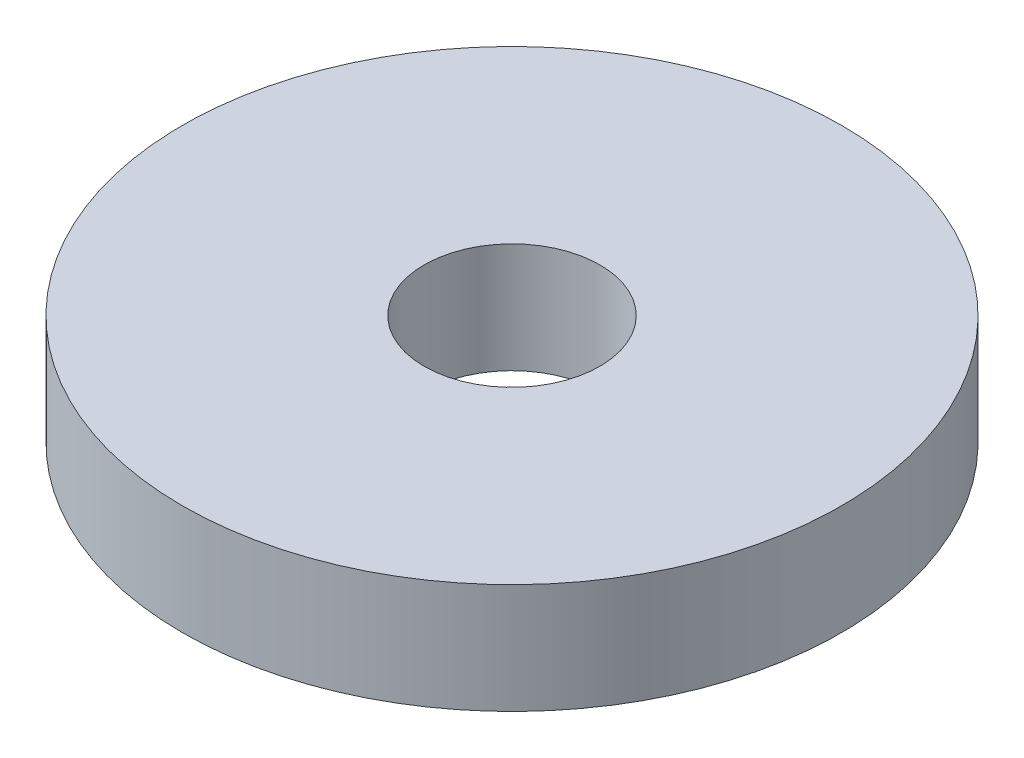
SolidWorks part; units mm, degrees
ref_plane "Front Plane" through (0, 0, 0) normal (0, 0, 1) x (1, 0, 0)
ref_plane "Top Plane" through (0, 0, 0) normal (0, 1, 0) x (1, 0, 0)
ref_plane "Right Plane" through (0, 0, 0) normal (1, 0, 0) x (0, 0, -1)
sketch "Sketch1" plane through (0, 0, 0) normal (0, 1, 0) x (1, 0, 0)
  circle A0 centre (0, 0) radius 4
  circle A1 centre (0, 0) radius 15
  dimension "D1" = 8
  dimension "D2" = 30
extrude "Boss-Extrude1" add sketch "Sketch1" along normal blind 5
